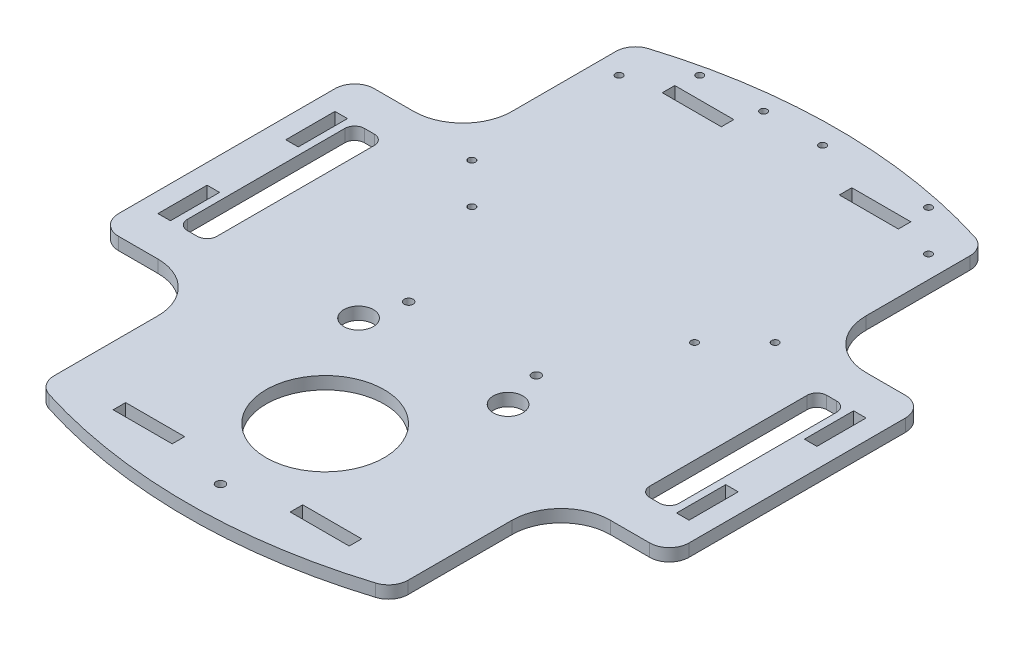
SolidWorks part; units mm, degrees
ref_plane "Plan de face" through (0, 0, 0) normal (0, 0, 1) x (1, 0, 0)
ref_plane "Plan de dessus" through (0, 0, 0) normal (0, 1, 0) x (1, 0, 0)
ref_plane "Plan de droite" through (0, 0, 0) normal (1, 0, 0) x (0, 0, -1)
sketch "Esquisse1" plane through (0, 0, 0) normal (0, 1, 0) x (1, 0, 0)
  line L0 (-145, 0) -> (0, 0) construction
  line L1 (-90, -150) -> (90, -150)
  line L2 (-90, -150) -> (-90, 150)
  line L3 (-90, 150) -> (90, 150)
  line L4 (90, -150) -> (90, 150)
  line L5 (-90, -150) -> (90, 150) construction
  line L6 (-90, 150) -> (90, -150) construction
  line L7 (-90, 65) -> (-145, 65)
  line L8 (-90, 65) -> (-90, -65)
  line L9 (-90, -65) -> (-145, -65)
  line L10 (-145, 65) -> (-145, -65)
  line L11 (0, 0) -> (0, -275) construction
  line L12 (90, -65) -> (145, -65)
  line L13 (145, 65) -> (145, -65)
  line L14 (90, 65) -> (145, 65)
  line L15 (90, 65) -> (90, -65)
  arc A0 (-90, 150) -> (90, 150) centre (0, -112.5) cw
  arc A1 (-90, -150) -> (90, -150) centre (0, 112.5) ccw
  point P0 (0, 0)
  point P19 (0, 165)
  point P20 (0, -165)
  dimension "D1" = 180
  dimension "D2" = 300
  dimension "D3" = 85
  dimension "D4" = 55
  dimension "D5" = 15
  dimension "D6" = 15
extrude "Boss.-Extru.1" add sketch "Esquisse1" along normal blind 6.35 contours L1 L4 L3 L2 | L7 L10 L9 L2 | L14 L4 L12 L13 | L1 A1 | A0 L3
ref_plane "Plan1" through (0, 0, 150) normal (0, 0, -1) x (-1, 0, 0)
ref_plane "Plan3" through (0, 0, -150) normal (0, 0, -1) x (-1, 0, 0)
ref_plane "Wheel axis1" through (0, 0, 107.5) normal (0, 0, 1) x (1, 0, 0)
ref_plane "Wheel axis2" through (0, 0, -107.5) normal (0, 0, -1) x (-1, 0, 0)
fillet "Congé1" radius 25 4 edges at (90, 3.175, -65) (-90, 3.175, -65) (-90, 3.175, 65) (90, 3.175, 65)
fillet "Congé2" radius 10 8 edges at (-90, 3.175, -150) (-145, 3.175, -65) (-145, 3.175, 65) (-90, 3.175, 150) (90, 3.175, -150) (145, 3.175, -65) (145, 3.175, 65) (90, 3.175, 150)
sketch "Esquisse2" plane through (0, 6.35, 0) normal (0, 1, 0) x (1, 0, 0)
  line L0 (0, 0) -> (0, -95) construction
  circle A0 centre (0, -95) radius 30
  dimension "D1" = 60
  dimension "D2" = 95
extrude "Enlèv. mat.-Extru.1" cut sketch "Esquisse2" against normal up to next
sketch "Esquisse3" plane through (0, 6.35, 0) normal (0, 1, 0) x (1, 0, 0)
  circle A0 centre (-32.4307, -20.0639) radius 2.25 construction
  circle A1 centre (32.4307, -20.0639) radius 2.25 construction
  circle A2 centre (0, -148.1871) radius 2.25 construction
  circle A3 centre (-32.4307, -20.0639) radius 2.25
  circle A4 centre (32.4307, -20.0639) radius 2.25
  circle A5 centre (0, -148.1871) radius 2.25
extrude "Enlèv. mat.-Extru.2" cut sketch "Esquisse3" against normal up to next
sketch "Esquisse5" plane through (0, 6.35, 0) normal (0, 1, 0) x (1, 0, 0)
  line L0 (-30, 136.4072) -> (-30, 142.7572) construction
  line L1 (-30, 142.7572) -> (-60, 142.7572) construction
  line L2 (-60, 142.7572) -> (-60, 136.4072) construction
  line L3 (-60, 136.4072) -> (-30, 136.4072) construction
  line L4 (60, 136.4072) -> (60, 142.7572) construction
  line L5 (60, 142.7572) -> (30, 142.7572) construction
  line L6 (30, 142.7572) -> (30, 136.4072) construction
  line L7 (30, 136.4072) -> (60, 136.4072) construction
  line L8 (-30, -142.7572) -> (-30, -136.4072) construction
  line L9 (-30, -136.4072) -> (-60, -136.4072) construction
  line L10 (-60, -136.4072) -> (-60, -142.7572) construction
  line L11 (-60, -142.7572) -> (-30, -142.7572) construction
  line L12 (60, -142.7572) -> (60, -136.4072) construction
  line L13 (60, -136.4072) -> (30, -136.4072) construction
  line L14 (30, -136.4072) -> (30, -142.7572) construction
  line L15 (30, -142.7572) -> (60, -142.7572) construction
  line L16 (135, -20) -> (128.65, -20) construction
  line L17 (128.65, -20) -> (128.65, -45) construction
  line L18 (128.65, -45) -> (135, -45) construction
  line L19 (135, -45) -> (135, -20) construction
  line L20 (135, 45) -> (128.65, 45) construction
  line L21 (128.65, 45) -> (128.65, 20) construction
  line L22 (128.65, 20) -> (135, 20) construction
  line L23 (135, 20) -> (135, 45) construction
  line L24 (-128.65, 45) -> (-135, 45) construction
  line L25 (-135, 45) -> (-135, 20) construction
  line L26 (-135, 20) -> (-128.65, 20) construction
  line L27 (-128.65, 20) -> (-128.65, 45) construction
  line L28 (-128.65, -20) -> (-135, -20) construction
  line L29 (-135, -20) -> (-135, -45) construction
  line L30 (-135, -45) -> (-128.65, -45) construction
  line L31 (-128.65, -45) -> (-128.65, -20) construction
  line L32 (-30, 136.4072) -> (-30, 142.7572)
  line L33 (-30, 142.7572) -> (-60, 142.7572)
  line L34 (-60, 142.7572) -> (-60, 136.4072)
  line L35 (-60, 136.4072) -> (-30, 136.4072)
  line L36 (60, 136.4072) -> (60, 142.7572)
  line L37 (60, 142.7572) -> (30, 142.7572)
  line L38 (30, 142.7572) -> (30, 136.4072)
  line L39 (30, 136.4072) -> (60, 136.4072)
  line L40 (-30, -142.7572) -> (-30, -136.4072)
  line L41 (-30, -136.4072) -> (-60, -136.4072)
  line L42 (-60, -136.4072) -> (-60, -142.7572)
  line L43 (-60, -142.7572) -> (-30, -142.7572)
  line L44 (60, -142.7572) -> (60, -136.4072)
  line L45 (60, -136.4072) -> (30, -136.4072)
  line L46 (30, -136.4072) -> (30, -142.7572)
  line L47 (30, -142.7572) -> (60, -142.7572)
  line L48 (135, -20) -> (128.65, -20)
  line L49 (128.65, -20) -> (128.65, -45)
  line L50 (128.65, -45) -> (135, -45)
  line L51 (135, -45) -> (135, -20)
  line L52 (135, 45) -> (128.65, 45)
  line L53 (128.65, 45) -> (128.65, 20)
  line L54 (128.65, 20) -> (135, 20)
  line L55 (135, 20) -> (135, 45)
  line L56 (-128.65, 45) -> (-135, 45)
  line L57 (-135, 45) -> (-135, 20)
  line L58 (-135, 20) -> (-128.65, 20)
  line L59 (-128.65, 20) -> (-128.65, 45)
  line L60 (-128.65, -20) -> (-135, -20)
  line L61 (-135, -20) -> (-135, -45)
  line L62 (-135, -45) -> (-128.65, -45)
  line L63 (-128.65, -45) -> (-128.65, -20)
extrude "Enlèv. mat.-Extru.3" cut sketch "Esquisse5" against normal up to next
sketch "Esquisse6" plane through (0, 6.35, 0) normal (0, 1, 0) x (1, 0, 0)
  line L0 (0, 0) -> (0, -40) construction
  line L1 (0, -40) -> (-38, -40) construction
  line L2 (0, -40) -> (38, -40) construction
  circle A0 centre (38, -40) radius 7.5
  circle A1 centre (-38, -40) radius 7.5
  dimension "D1" = 15
  dimension "D2" = 40
  dimension "D3" = 38
extrude "Enlèv. mat.-Extru.4" cut sketch "Esquisse6" against normal up to next
sketch "Esquisse7" plane through (0, 6.35, 0) normal (0, 1, 0) x (1, 0, 0)
  line L0 (-128.65, 45) -> (-135, 45) construction
  line L1 (-120, 45) -> (-115, 45)
  line L2 (-125, 40) -> (-125, -40)
  line L3 (-120, -45) -> (-115, -45)
  line L4 (-110, 40) -> (-110, -40)
  line L5 (-135, -45) -> (-128.65, -45) construction
  line L6 (0, 0) -> (0, -19.9046) construction
  line L7 (120, -45) -> (115, -45)
  line L8 (110, 40) -> (110, -40)
  line L9 (120, 45) -> (115, 45)
  line L10 (125, 40) -> (125, -40)
  arc A0 (-120, 45) -> (-125, 40) centre (-120, 40) ccw
  arc A1 (-115, 45) -> (-110, 40) centre (-115, 40) cw
  arc A2 (-115, -45) -> (-110, -40) centre (-115, -40) ccw
  arc A3 (-125, -40) -> (-120, -45) centre (-120, -40) ccw
  arc A4 (115, -45) -> (110, -40) centre (115, -40) cw
  arc A5 (115, 45) -> (110, 40) centre (115, 40) ccw
  arc A6 (120, 45) -> (125, 40) centre (120, 40) cw
  arc A7 (125, -40) -> (120, -45) centre (120, -40) cw
  point P11 (-125, 45)
  point P14 (-110, 45)
  dimension "D3" = 5
  dimension "D1" = 110
  dimension "D2" = 15
extrude "Enlèv. mat.-Extru.5" cut sketch "Esquisse7" against normal up to next
sketch "Esquisse8" plane through (0, 6.35, 0) normal (0, 1, 0) x (1, 0, 0)
  circle A0 centre (-78.7146, 58.3156) radius 1.8 construction
  circle A1 centre (-58.2146, 37.8156) radius 1.8 construction
  circle A2 centre (58.1719, 34.6406) radius 1.8 construction
  circle A3 centre (78.6719, 55.1406) radius 1.8 construction
  circle A4 centre (78.6719, 133.0906) radius 1.8 construction
  circle A5 centre (58.1719, 153.5906) radius 1.8 construction
  circle A6 centre (3.8875, 154) radius 1.8 construction
  circle A7 centre (-26.1125, 154) radius 1.8 construction
  circle A8 centre (-58.1719, 153.5906) radius 1.8 construction
  circle A9 centre (-78.6719, 133.0906) radius 1.8 construction
  circle A10 centre (-78.7146, 58.3156) radius 1.8
  circle A11 centre (-58.2146, 37.8156) radius 1.8
  circle A12 centre (58.1719, 34.6406) radius 1.8
  circle A13 centre (78.6719, 55.1406) radius 1.8
  circle A14 centre (78.6719, 133.0906) radius 1.8
  circle A15 centre (58.1719, 153.5906) radius 1.8
  circle A16 centre (3.8875, 154) radius 1.8
  circle A17 centre (-26.1125, 154) radius 1.8
  circle A18 centre (-58.1719, 153.5906) radius 1.8
  circle A19 centre (-78.6719, 133.0906) radius 1.8
extrude "Enlèv. mat.-Extru.6" cut sketch "Esquisse8" against normal up to next
